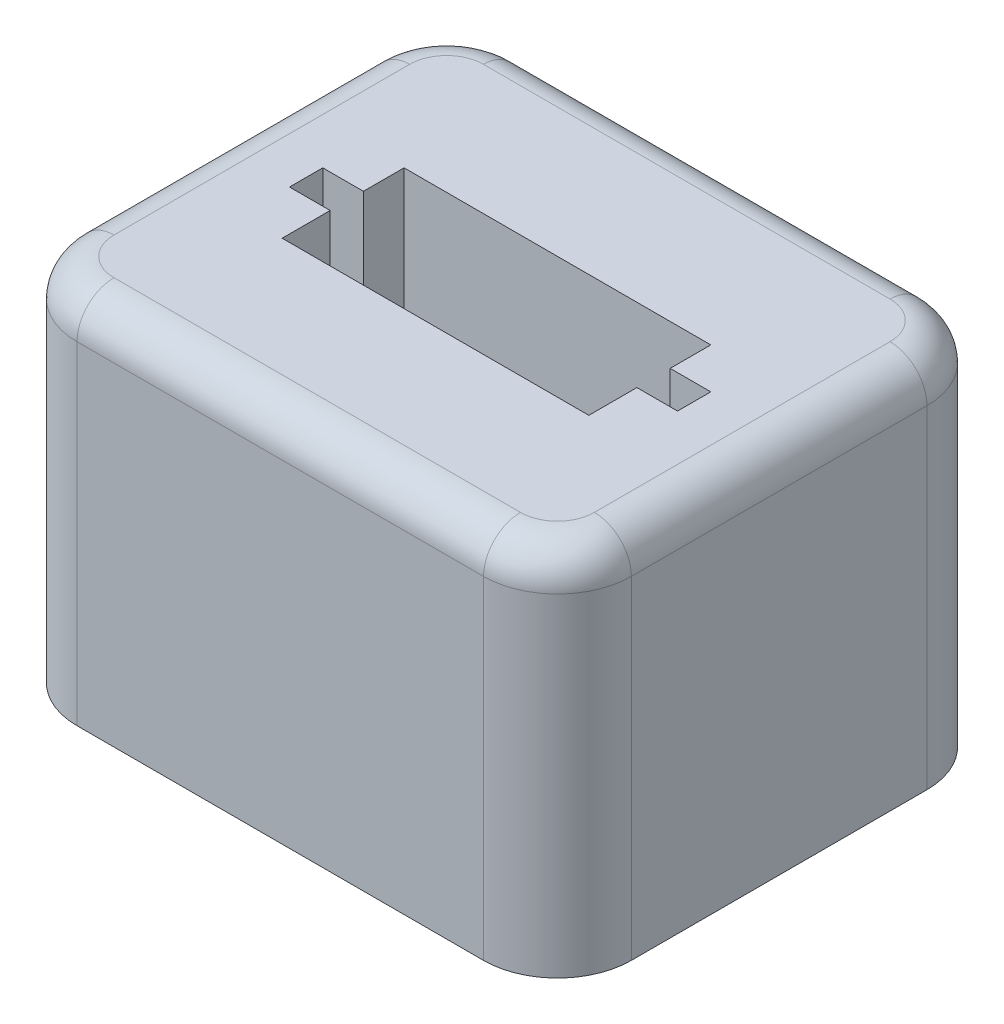
SolidWorks part; units mm, degrees
ref_plane "Спереди" through (0, 0, 0) normal (0, 0, 1) x (1, 0, 0)
ref_plane "Сверху" through (0, 0, 0) normal (0, 1, 0) x (1, 0, 0)
ref_plane "Справа" through (0, 0, 0) normal (1, 0, 0) x (0, 0, -1)
sketch "Эскиз1" plane through (0, 0, 0) normal (0, 1, 0) x (1, 0, 0)
  line L1 (4, 0) -> (26, 0)
  line L2 (0, 4) -> (0, 20)
  line L3 (4, 24) -> (26, 24)
  line L4 (30, 4) -> (30, 20)
  arc A0 (26, 24) -> (30, 20) centre (26, 20) cw
  arc A1 (26, 0) -> (30, 4) centre (26, 4) ccw
  arc A2 (4, 0) -> (0, 4) centre (4, 4) cw
  arc A3 (0, 20) -> (4, 24) centre (4, 20) cw
  point P10 (30, 0)
  point P13 (0, 0)
  point P16 (0, 24)
  dimension "D3" = 4
  dimension "D1" = 30
  dimension "D2" = 24
extrude "Тело" add sketch "Эскиз1" along normal blind 20
fillet "Скругление1" radius 2 8 edges at (15, 20, 0) (28.8284, 20, -1.1716) (1.1716, 20, -1.1716) (0, 20, -12) (1.1716, 20, -22.8284) (15, 20, -24) (28.8284, 20, -22.8284) (30, 20, -12)
sketch "Эскиз6" plane through (0, 0, 0) normal (0, -1, 0) x (1, 0, 0)
  circle A0 centre (4, -4) radius 1
  circle A1 centre (26, -4) radius 1
  circle A2 centre (26, -20) radius 1
  circle A3 centre (4, -20) radius 1
  dimension "D1" = 2
extrude "Крепеж" cut sketch "Эскиз6" against normal blind 7
sketch "Эскиз3" plane through (0, 20, 0) normal (0, 1, 0) x (1, 0, 0)
  line L1 (6.7, 11.4) -> (23.3, 11.4)
  line L2 (6.7, 11.4) -> (6.7, 8.4)
  line L3 (6.7, 8.4) -> (23.3, 8.4)
  line L4 (23.3, 11.4) -> (23.3, 8.4)
  line L5 (4, 0) -> (26, 0) construction
  point P7 (15, 0)
  point P11 (15, 8.4)
  dimension "D1" = 16.6
  dimension "D2" = 3
  dimension "D3" = 8.4
extrude "Разъем" cut sketch "Эскиз3" against normal up to next
sketch "Эскиз2" plane through (0, 20, 0) normal (0, 1, 0) x (1, 0, 0)
  line L1 (4.5, 12.8) -> (25.5, 12.8)
  line L2 (4.5, 12.8) -> (4.5, 11)
  line L3 (4.5, 11) -> (25.5, 11)
  line L4 (25.5, 12.8) -> (25.5, 11)
  line L5 (23.3, 11.4) -> (6.7, 11.4) construction
  point P4 (15, 11)
  point P11 (15, 11.4)
  dimension "D1" = 1.8
  dimension "D2" = 21
  dimension "D3" = 0.4
extrude "Плата" cut sketch "Эскиз2" against normal offset from surface (12 mm away) 8 up to face at (15, 0, -9.9)
sketch "Эскиз7" plane through (0, 20, 0) normal (0, 1, 0) x (1, 0, 0)
  line L0 (25.5, 12.8) -> (4.5, 12.8) construction
  line L1 (6.7, 12.8) -> (23.3, 12.8)
  line L2 (6.7, 12.8) -> (6.7, 15)
  line L3 (6.7, 15) -> (23.3, 15)
  line L4 (23.3, 12.8) -> (23.3, 15)
  line L5 (6.7, 11) -> (6.7, 8.4) construction
  line L6 (23.3, 8.4) -> (23.3, 11) construction
  dimension "D1" = 2.2
extrude "Вырез-Вытянуть1" cut sketch "Эскиз7" against normal up to surface (12 mm away) up to face at (15, 8, -11.55)
